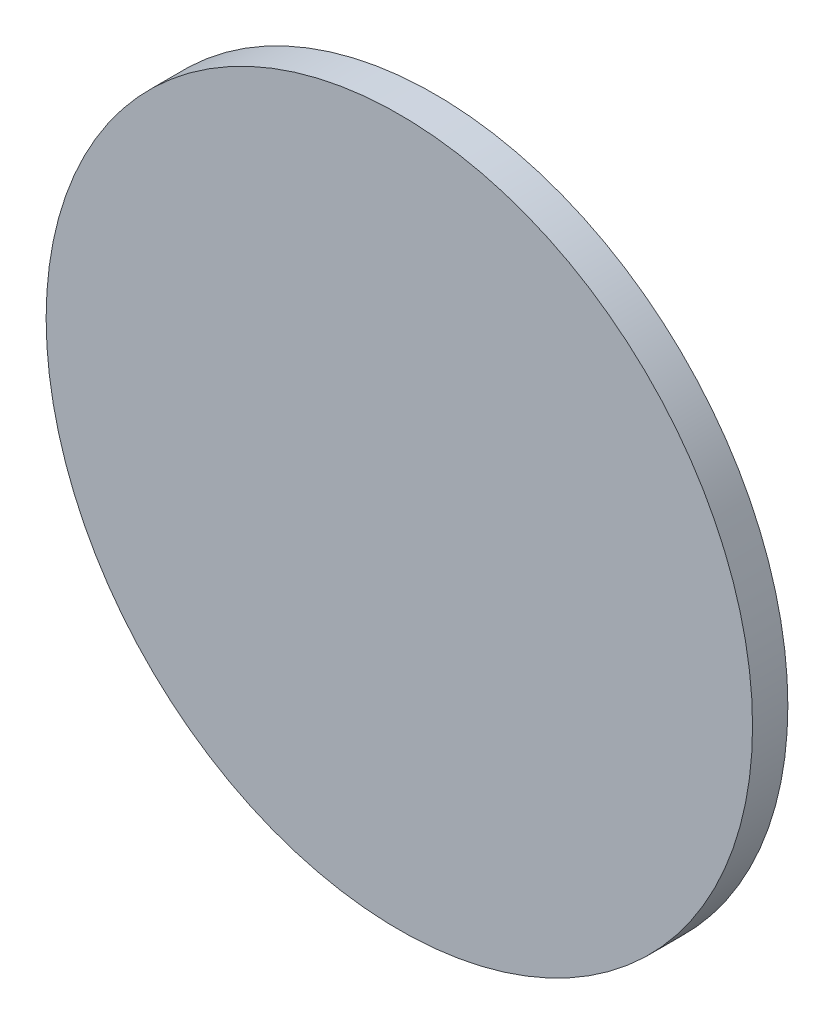
SolidWorks part; units mm, degrees
material "ABS PC"
ref_plane "Front Plane" through (0, 0, 0) normal (0, 0, 1) x (1, 0, 0)
ref_plane "Top Plane" through (0, 0, 0) normal (0, 1, 0) x (1, 0, 0)
ref_plane "Right Plane" through (0, 0, 0) normal (1, 0, 0) x (0, 0, -1)
sketch "Sketch1" plane through (0, 0, 0) normal (0, 0, 1) x (1, 0, 0)
  circle A0 centre (0, 0) radius 2
  dimension "D1" = 4
extrude "Boss-Extrude1" add sketch "Sketch1" along normal blind 0.2
